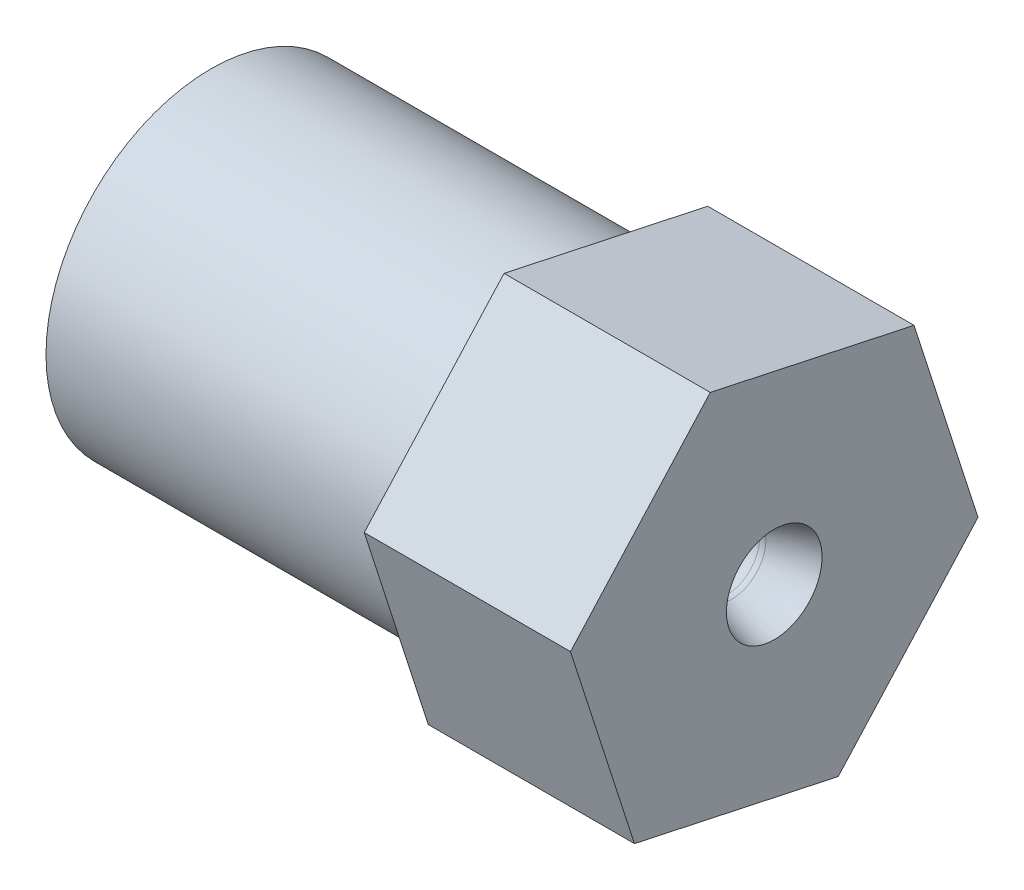
SolidWorks part; units mm, degrees
ref_plane "Front Plane" through (0, 0, 0) normal (0, 0, 1) x (1, 0, 0)
ref_plane "Top Plane" through (0, 0, 0) normal (0, 1, 0) x (1, 0, 0)
ref_plane "Right Plane" through (0, 0, 0) normal (1, 0, 0) x (0, 0, -1)
sketch "Sketch1" plane through (0, 0, 0) normal (0, 0, 1) x (1, 0, 0)
  line L0 (0, 0) -> (2.9335, 0) construction
  line L1 (0.3176, 2.0966) -> (2.9335, 3.207) construction
  line L2 (-2.1553, 2.9247) -> (-2.7456, 3.5151)
  line L3 (-31.75, 4.445) -> (-31.75, 10.16) construction
  line L4 (-4.9907, 4.445) -> (-31.75, 4.445) construction
  line L5 (-31.75, 10.16) -> (-9.7665, 10.16)
  line L6 (2.9335, 10.16) -> (2.9335, 2.9446)
  line L7 (2.9335, 2.9446) -> (12.698, 5.199) construction
  line L8 (-9.7665, 10.16) -> (2.9335, 10.16)
  line L9 (-4.9907, 4.445) -> (-13.462, 4.445)
  line L10 (-19.939, 5.461) -> (-19.939, 6.8199)
  line L11 (-20.066, 6.9469) -> (-24.892, 6.9469)
  line L12 (-24.892, 6.9469) -> (-24.892, 7.8994)
  line L13 (-25.019, 8.0264) -> (-31.115, 8.0264)
  line L14 (-31.75, 10.16) -> (-31.75, 8.6614)
  line L15 (0, 0) -> (-31.75, 0) construction
  line L16 (-13.462, 4.445) -> (-13.462, 4.699)
  line L17 (-13.589, 4.826) -> (-19.304, 4.826)
  arc A0 (-2.1553, 2.9247) -> (0, 2.032) centre (0, 5.08) ccw
  arc A1 (0, 2.032) -> (0.3176, 2.0966) centre (0, 2.8448) ccw
  arc A2 (-2.7456, 3.5151) -> (-4.9907, 4.445) centre (-4.9907, 1.27) ccw
  arc A3 (-31.115, 8.0264) -> (-31.75, 8.6614) centre (-31.115, 8.6614) cw
  arc A4 (-19.304, 4.826) -> (-19.939, 5.461) centre (-19.304, 5.461) cw
  arc A5 (-13.462, 4.699) -> (-13.589, 4.826) centre (-13.589, 4.699) ccw
  arc A6 (-19.939, 6.8199) -> (-20.066, 6.9469) centre (-20.066, 6.8199) ccw
  arc A7 (-24.892, 7.8994) -> (-25.019, 8.0264) centre (-25.019, 7.8994) ccw
  parabola Q0 (2.9335, 2.9446) -> (0.3176, 2.0966) focus (3.3527, -5.0537) apex (0.3176, 2.0966)
  point P30 (-31.75, 8.0264)
  point P39 (-24.892, 8.0264)
  dimension "D3" = 3.048
  dimension "D4" = 0.8128
  dimension "D11" = 3.175
  dimension "D12" = 13
  dimension "D14" = 6.9469
  dimension "D20" = 0.635
  dimension "D21" = 0.127
  dimension "D2" = 2.9335
  dimension "D5" = 2.9446
  dimension "D6" = 23
  dimension "D7" = 45
  dimension "D8" = 8.0264
  dimension "D9" = 31.75
  dimension "D10" = 10.16
  dimension "D13" = 12.7
  dimension "D15" = 4.445
  dimension "D16" = 6.858
  dimension "D17" = 11.811
  dimension "D18" = 18.288
  dimension "D19" = 4.826
  dimension "D22" = 2.032
revolve "Revolve1" add sketch "Sketch1" angle 360 about L0
sketch "Sketch4" plane through (2.9335, 0, 0) normal (1, 0, 0) x (0, 0, -1)
  line L1 (3.9404, -12.2116) -> (12.5458, -2.6933)
  line L2 (12.5458, -2.6933) -> (8.6054, 9.5183)
  line L3 (8.6054, 9.5183) -> (-3.9404, 12.2116)
  line L4 (-3.9404, 12.2116) -> (-12.5458, 2.6933)
  line L5 (-12.5458, 2.6933) -> (-8.6054, -9.5183)
  line L6 (-8.6054, -9.5183) -> (3.9404, -12.2116)
  circle A0 centre (0, 0) radius 10.16
  circle A1 centre (0, 0) radius 10.16 construction
  circle A2 centre (0, 0) radius 11.1125 construction
  circle M1 centre (0, 0) radius 10.16
  dimension "D1" = 22.225
extrude "Boss-Extrude1" add sketch "Sketch4" against normal blind 12.7 contours L4 L5 M1 | L3 L4 M1 | L2 L3 M1 | L1 L2 M1 | L6 L1 M1 | L5 L6 M1
fillet "Fillet1" radius 0.635 1 edges at (-9.7665, 0, -10.16)
equation "\"D3@Sketch1\" = 1.5 * \"D22@Sketch1\""
equation "\"D4@Sketch1\"  = .4 * \"D22@Sketch1\""
equation "\"D5@Sketch1\"=\"D22@Sketch1\" * ( \"er\") ^ .5"
equation "\"er\"= 2.1"
